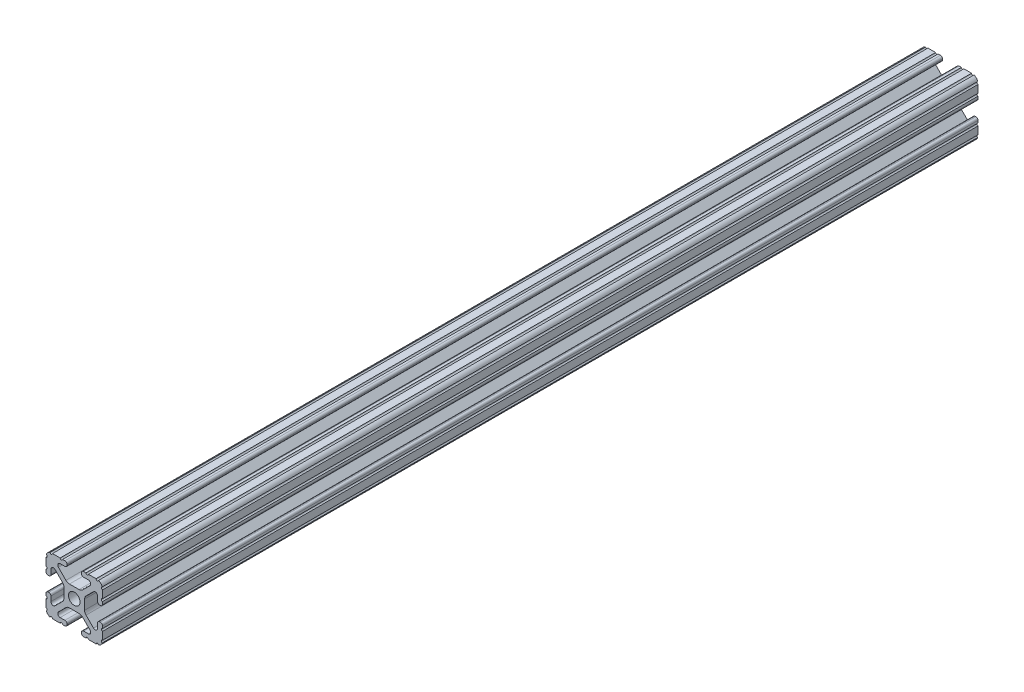
SolidWorks part; units mm, degrees
ref_plane "Front Plane" through (0, 0, 0) normal (0, 0, 1) x (1, 0, 0)
ref_plane "Top Plane" through (0, 0, 0) normal (0, 1, 0) x (1, 0, 0)
ref_plane "Right Plane" through (0, 0, 0) normal (1, 0, 0) x (0, 0, -1)
sketch "Sketch2" plane through (0, 0, 0) normal (0, 0, 1) x (1, 0, 0)
  line L0 (0, 12.7) -> (0, -12.7) construction
  line L1 (-12.7, 0) -> (12.7, 0) construction
  line L2 (3.2512, -12.7) -> (12.7, -12.7)
  line L3 (12.7, -12.7) -> (12.7, -3.2512)
  line L4 (3.2512, -12.7) -> (3.2512, -10.4902)
  line L5 (3.2512, -10.4902) -> (8.9276, -10.4902)
  line L6 (8.9276, -10.4902) -> (3.0856, -4.6482)
  line L7 (0, 0) -> (12.7, -12.7) construction
  line L8 (12.7, -3.2512) -> (10.4902, -3.2512)
  line L9 (10.4902, -3.2512) -> (10.4902, -8.9276)
  line L10 (10.4902, -8.9276) -> (4.6482, -3.0856)
  circle A0 centre (0, 0) radius 2.6035
  arc A1 (6.3485, -10.4902) -> (7.1039, -8.6665) centre (6.3485, -9.4219) ccw construction
  point P8 (0, -4.6482)
  dimension "Center Hole Diameter" = 5.207
  dimension "Rail Height" = 25.4
  dimension "Rail Width" = 25.4
  dimension "T-Slot Width" = 6.5024
  dimension "Slot Inner Width" = 14.8336
  dimension "Thickness" = 2.2098
  dimension "Slot Depth" = 5.842
  dimension "D1" = 2.2098
sketch "Sketch3" plane through (0, 0, 0) normal (1, 0, 0) x (0, 0, -1)
  line L0 (-196.8198, -12.7) -> (196.8198, -12.7) construction
  line L1 (-171.4198, 0) -> (171.4198, 0) construction
  line L3 (196.8198, 0) -> (-196.8198, 0) construction
sketch "Sketch4" plane through (0, 0, 0) normal (0, 0, 1) x (1, 0, 0)
  line L0 (4.1904, -12.7) -> (10.1173, -12.7)
  line L1 (3.2512, -12.7) -> (12.7, -12.7) construction
  line L2 (3.2512, -12.7) -> (3.2512, -10.4902) construction
  line L3 (3.2512, -10.4902) -> (8.9276, -10.4902) construction
  line L4 (3.2512, -11.4294) -> (3.2512, -11.7608)
  line L5 (4.1904, -10.4902) -> (6.3485, -10.4902)
  line L6 (0, -4.6482) -> (2.164, -4.6482)
  line L7 (8.9276, -10.4902) -> (3.0856, -4.6482) construction
  line L8 (3.7373, -5.2999) -> (7.1039, -8.6665)
  line L9 (12.7, -12.7) -> (12.7, -3.2512) construction
  line L10 (10.4902, -8.9276) -> (4.6482, -3.0856) construction
  line L11 (10.4902, -3.2512) -> (10.4902, -8.9276) construction
  line L12 (10.4902, -6.3485) -> (10.4902, -4.1904)
  line L13 (12.7, -3.2512) -> (10.4902, -3.2512) construction
  line L14 (11.4294, -3.2512) -> (11.7608, -3.2512)
  line L15 (12.7, -4.1904) -> (12.7, -10.1173)
  line L16 (8.6665, -7.1039) -> (5.2999, -3.7373)
  line L17 (4.6482, 0) -> (4.6482, -2.164)
  line L18 (-12.7, 0) -> (12.7, 0) construction
  line L19 (0, -4.6482) -> (0, -2.6035)
  line L20 (0, 12.7) -> (0, -12.7) construction
  line L21 (4.6482, 0) -> (2.6035, 0)
  arc A0 (3.2512, -11.7608) -> (4.1904, -12.7) centre (4.1904, -11.7608) ccw
  arc A2 (3.2512, -11.4294) -> (4.1904, -10.4902) centre (4.1904, -11.4294) cw
  arc A3 (6.3485, -10.4902) -> (7.1039, -8.6665) centre (6.3485, -9.4219) ccw
  arc A4 (2.164, -4.6482) -> (3.7373, -5.2999) centre (2.164, -6.8732) cw
  arc A5 (10.1173, -12.7) -> (12.7, -10.1173) centre (10.1173, -10.1173) ccw
  arc A6 (8.6665, -7.1039) -> (10.4902, -6.3485) centre (9.4219, -6.3485) ccw
  arc A7 (10.4902, -4.1904) -> (11.4294, -3.2512) centre (11.4294, -4.1904) cw
  arc A8 (11.7608, -3.2512) -> (12.7, -4.1904) centre (11.7608, -4.1904) cw
  arc A9 (5.2999, -3.7373) -> (4.6482, -2.164) centre (6.8732, -2.164) cw
  circle A10 centre (0, 0) radius 2.6035 construction
  arc A11 (0, -2.6035) -> (2.6035, 0) centre (0, 0) ccw
  dimension "D1" = 2.5827
  dimension "D2" = 2.225
  dimension "D3" = 0.9392
extrude "Boss-Extrude1" add sketch "Sketch4" along normal up to vertex (196.8198 mm away) from vertex at -196.8198 starting at point (0, -12.7, -196.8198)
sketch "Sketch5" plane through (0, 0, 0) normal (0, 0, 1) x (1, 0, 0)
  line L0 (3.2512, -12.7) -> (12.7, -12.7) construction
  line L1 (4.1904, -10.4902) -> (6.3485, -10.4902) construction
  line L3 (0, 0) -> (12.7, -12.7) construction
  line L4 (6.3485, -10.4902) -> (6.3485, -12.7) construction
  line L5 (8.9276, -10.4902) -> (3.0856, -4.6482) construction
  circle A0 centre (10.3562, -12.7) radius 0.5524
  circle A1 centre (5.796, -12.7) radius 0.5524
  circle A2 centre (12.7, -10.3562) radius 0.5524
  circle A3 centre (12.7, -5.796) radius 0.5524
  point P10 (5.2694, -10.4902)
  point P12 (9.4219, -6.3485)
  dimension "D1" = 1.1049
extrude "Cut-Extrude1" cut sketch "Sketch5" against normal through all both and the other way through all
mirror "Mirror1" about plane through (0, 0, 0) normal (1, 0, 0) of bodies 137 134
mirror "Mirror2" about plane through (0, 0, 0) normal (0, 1, 0) of bodies 135
equation "\"D1@Sketch2\"=\"Thickness@Sketch2\""
equation "\"D2@Sketch4\"=\"Slot Inner Width@Sketch2\"*0.15"
equation "\"D1@Sketch4\"=\"D3@Sketch4\"*2.75"
equation "\"D3@Sketch4\"=\"Thickness@Sketch2\"*0.425"
equation "\"D1@Sketch5\"=\"Thickness@Sketch2\"*0.5"
equation "\"D1@Boss-Extrude1\"=\"Length@Sketch3\""
